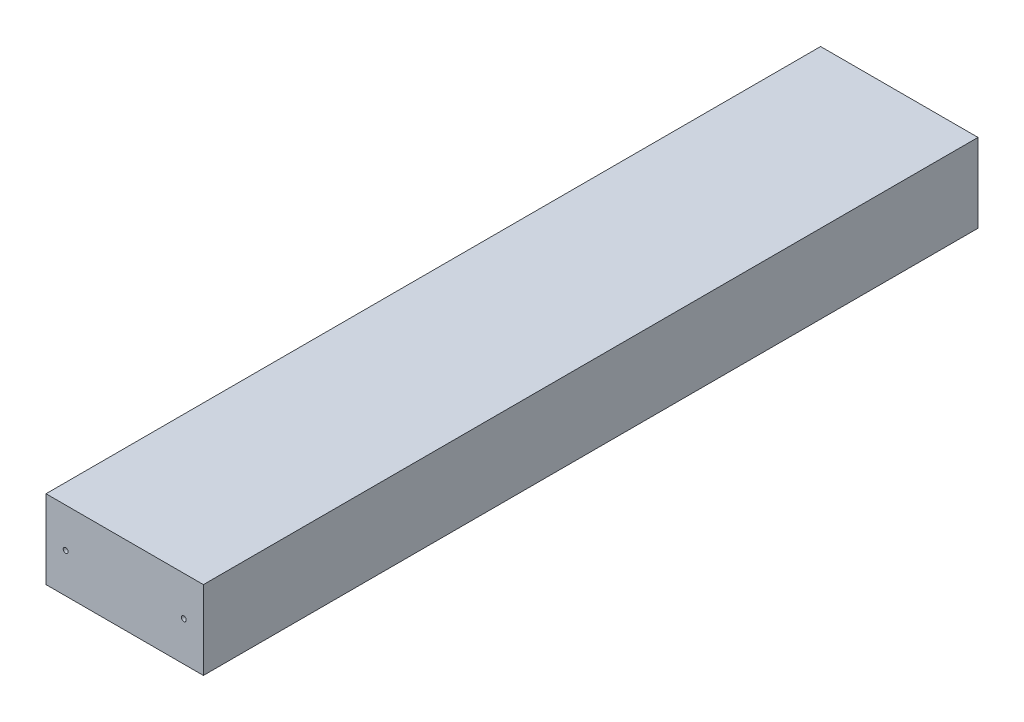
SolidWorks part; units mm, degrees
material "Pine"
ref_plane "Front Plane" through (0, 0, 0) normal (0, 0, 1) x (1, 0, 0)
ref_plane "Top Plane" through (0, 0, 0) normal (0, 1, 0) x (1, 0, 0)
ref_plane "Right Plane" through (0, 0, 0) normal (1, 0, 0) x (0, 0, -1)
sketch "Sketch1" plane through (0, 0, 0) normal (0, 0, 1) x (1, 0, 0)
  line L1 (-50.8, -25.4) -> (50.8, -25.4)
  line L2 (-50.8, -25.4) -> (-50.8, 25.4)
  line L3 (-50.8, 25.4) -> (50.8, 25.4)
  line L4 (50.8, -25.4) -> (50.8, 25.4)
  line L5 (-50.8, -25.4) -> (50.8, 25.4) construction
  line L6 (-50.8, 25.4) -> (50.8, -25.4) construction
  point P0 (0, 0)
  dimension "D1" = 50.8
  dimension "D2" = 101.6
extrude "Boss-Extrude1" add sketch "Sketch1" along normal blind 500
sketch "Sketch2" plane through (0, 0, 500) normal (0, 0, 1) x (1, 0, 0)
  line L0 (-50.8, 25.4) -> (-50.8, -25.4) construction
  line L1 (50.8, -25.4) -> (50.8, 25.4) construction
  line L3 (50.8, 25.4) -> (-50.8, 25.4) construction
  line L4 (38.1, 0) -> (-38.1, 0) construction
  circle A2 centre (-38.1, 0) radius 1.5875
  circle A3 centre (38.1, 0) radius 1.5875
  dimension "D1" = 12.7
  dimension "D2" = 12.7
  dimension "D3" = 3.175
  dimension "D4" = 25.4
extrude "Cut-Extrude1" cut sketch "Sketch2" against normal blind 44.45
ref_plane "Plane1" through (0, 0, 250) normal (0, 0, -1) x (-1, 0, 0)
mirror "Mirror1" about plane through (0, 0, 250) normal (0, 0, -1) of "Cut-Extrude1"
